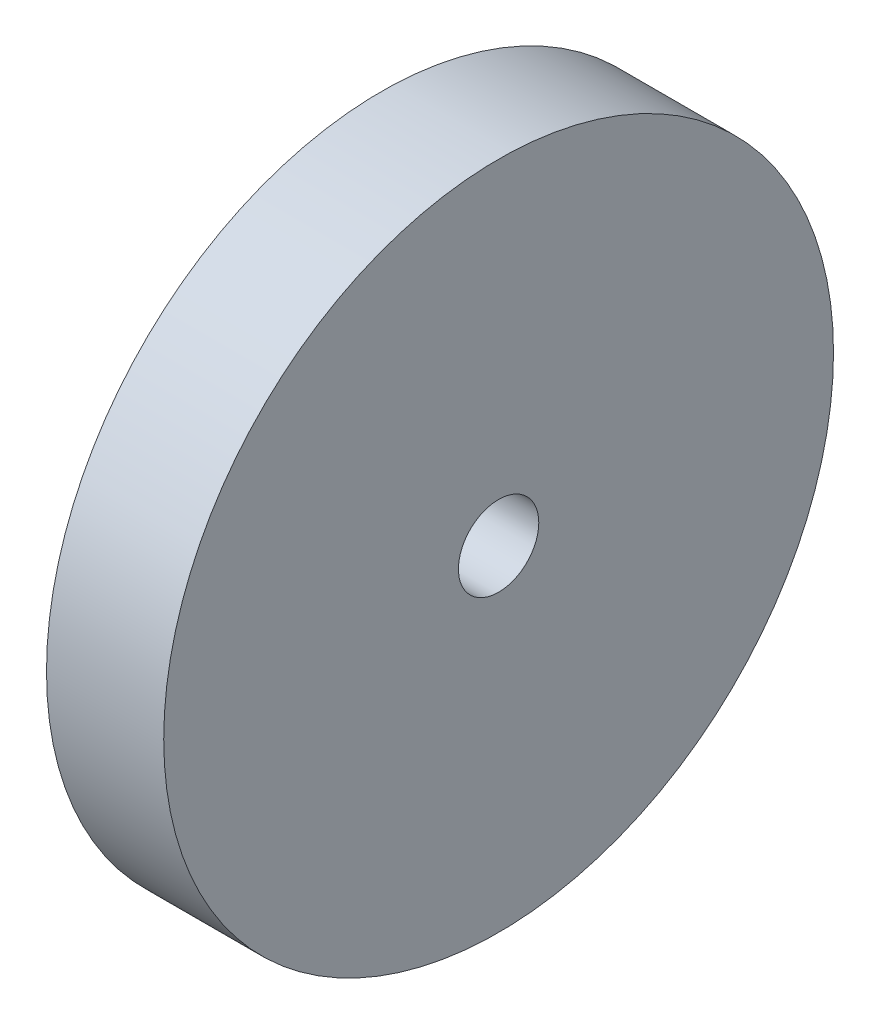
SolidWorks part; units mm, degrees
material "Maple"
ref_plane "Front Plane" through (0, 0, 0) normal (0, 0, 1) x (1, 0, 0)
ref_plane "Top Plane" through (0, 0, 0) normal (0, 1, 0) x (1, 0, 0)
ref_plane "Right Plane" through (0, 0, 0) normal (1, 0, 0) x (0, 0, -1)
sketch "Sketch1" plane through (0, 0, 0) normal (1, 0, 0) x (0, 0, -1)
  circle A0 centre (0, 0) radius 50
  circle A1 centre (0, 0) radius 6
  dimension "D1" = 100
  dimension "D2" = 12
extrude "Boss-Extrude1" add sketch "Sketch1" along normal blind 17.5
